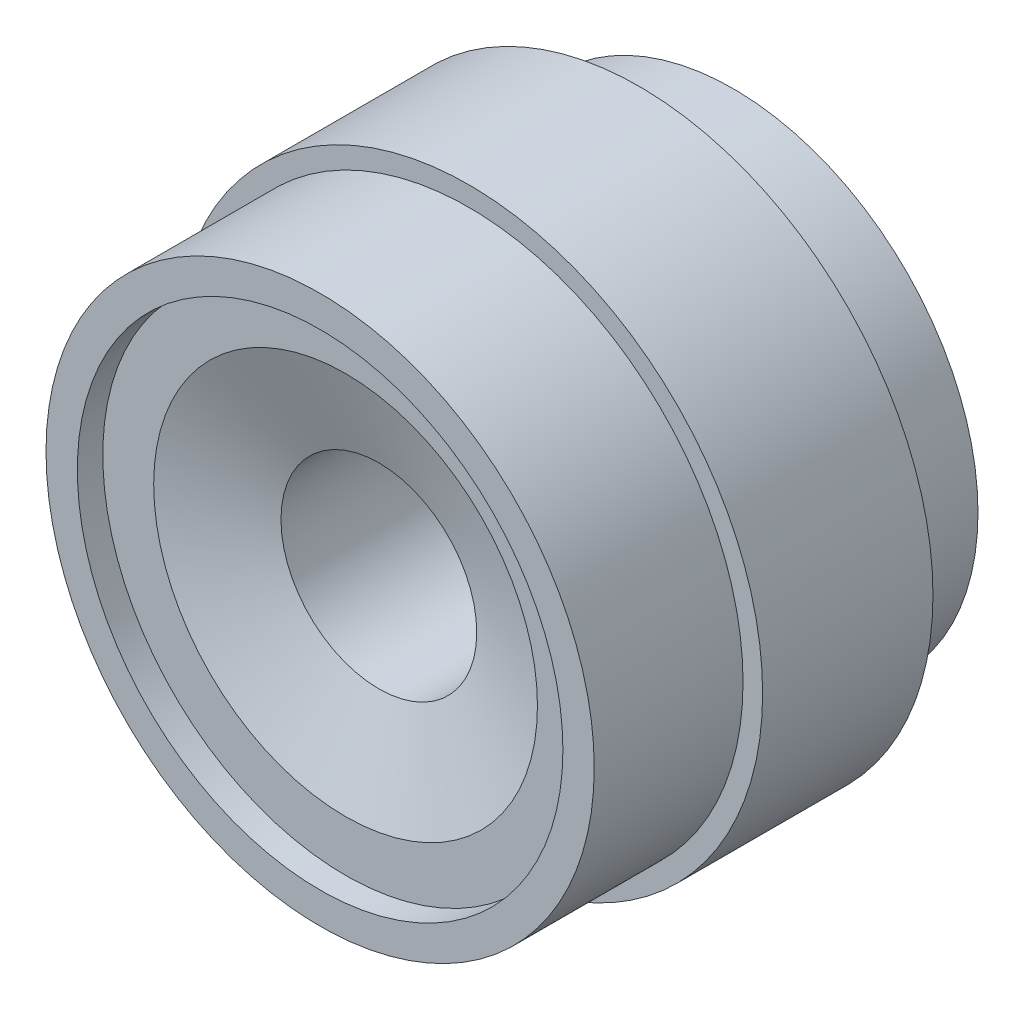
SolidWorks part; units mm, degrees
ref_plane "정면" through (0, 0, 0) normal (0, 0, 1) x (1, 0, 0)
ref_plane "윗면" through (0, 0, 0) normal (0, 1, 0) x (1, 0, 0)
ref_plane "우측면" through (0, 0, 0) normal (1, 0, 0) x (0, 0, -1)
sketch "스케치1" plane through (0, 0, 0) normal (0, 0, 1) x (1, 0, 0)
  circle A0 centre (0, 0) radius 12.5
  dimension "D1" = 25
extrude "보스-돌출1" add sketch "스케치1" along normal blind 4.8
sketch "스케치2" plane through (0, 0, 4.8) normal (0, 0, 1) x (1, 0, 0)
  circle A0 centre (0, 0) radius 15
  dimension "D1" = 30
extrude "보스-돌출2" add sketch "스케치2" along normal blind 8.7
sketch "스케치3" plane through (0, 0, 13.5) normal (0, 0, 1) x (1, 0, 0)
  circle A0 centre (0, 0) radius 14
  dimension "D1" = 28
extrude "보스-돌출3" add sketch "스케치3" along normal blind 7.6 contours A0
sketch "스케치5" plane through (0, 0, 0) normal (0, 1, 0) x (1, 0, 0)
  line L0 (0, -18.1) -> (5, -18.1)
  line L1 (5, -18.1) -> (9.8, -19.8)
  line L3 (9.8, -19.8) -> (12.4, -19.8)
  line L4 (12.4, -19.8) -> (12.4, -21.8295)
  line L5 (12.4, -21.8295) -> (0, -21.8295)
  line L6 (0, -21.8295) -> (0, -18.1)
  line L7 (-14, -21.1) -> (14, -21.1) construction
  dimension "D1" = 1.3
  dimension "D2" = 12.4
  dimension "D3" = 2.6
  dimension "D4" = 5
  dimension "D5" = 3
revolve "컷-회전1" cut sketch "스케치5" angle 360 about L6
sketch "스케치6" plane through (0, 0, 18.1) normal (0, 0, 1) x (1, 0, 0)
  circle A0 centre (0, 0) radius 5
extrude "컷-돌출1" cut sketch "스케치6" against normal through all
